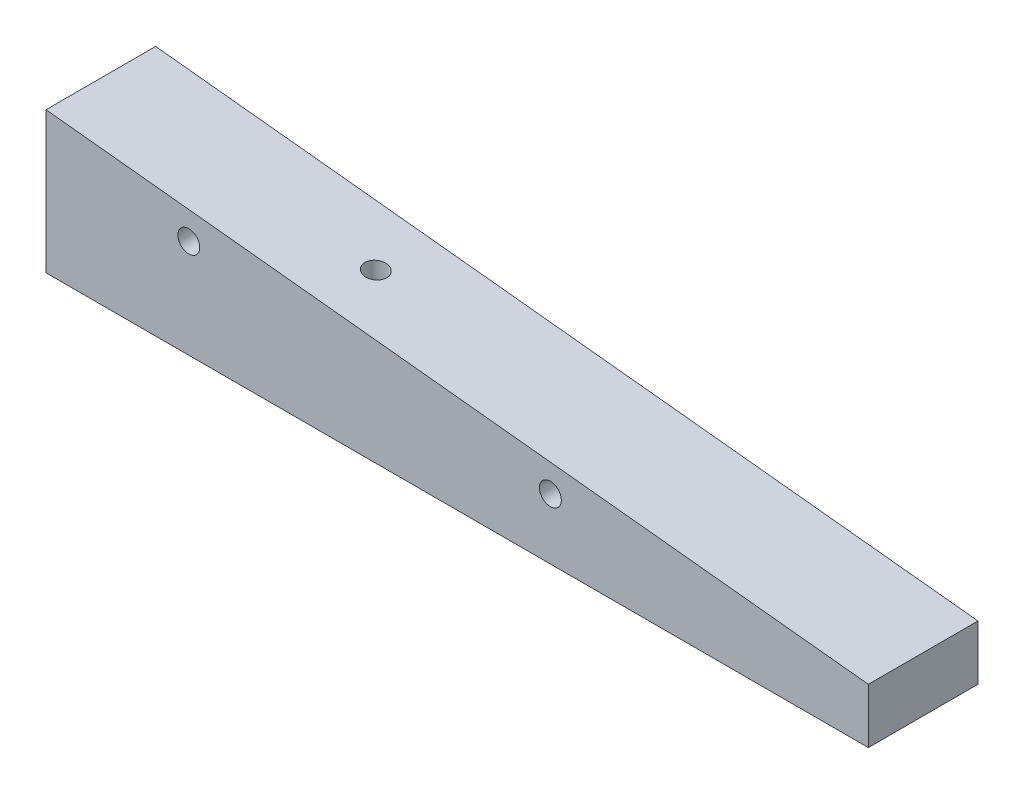
SolidWorks part; units mm, degrees
ref_plane "Front Plane" through (0, 0, 0) normal (0, 0, 1) x (1, 0, 0)
ref_plane "Top Plane" through (0, 0, 0) normal (0, 1, 0) x (1, 0, 0)
ref_plane "Right Plane" through (0, 0, 0) normal (1, 0, 0) x (0, 0, -1)
sketch "Sketch1" plane through (0, 0, 0) normal (0, 0, 1) x (1, 0, 0)
  line L2 (99.8523, 10) -> (-50.1477, 25.7656)
  line L4 (99.8523, 10) -> (99.8523, 0)
  line L5 (99.8523, 0) -> (-50.1477, 0)
  line L6 (-50.1477, 0) -> (-50.1477, 25.7656)
  line L7 (55, 0) -> (-55, 0) construction
  point P0 (0, 0)
  dimension "D1" = 150
  dimension "D2" = 6
  dimension "D3" = 10
extrude "Boss-Extrude1" add sketch "Sketch1" along normal mid plane 20
sketch "Sketch2" plane through (0, 0, 0) normal (0, -1, 0) x (1, 0, 0)
  circle A0 centre (0, 0) radius 2
  dimension "D1" = 4
extrude "Cut-Extrude1" cut sketch "Sketch2" against normal through all both and the other way through all
sketch "Sketch3" plane through (0, 0, -10) normal (0, 0, -1) x (-1, 0, 0)
  line L0 (-42.3716, 16.0415) -> (-41.849, 11.0689) construction
  line L1 (-99.8523, 10) -> (50.1477, 25.7656) construction
  line L2 (23.5813, 22.9734) -> (24.1039, 18.0008) construction
  circle A0 centre (24.1039, 18.0008) radius 2
  circle A1 centre (-41.849, 11.0689) radius 2
  dimension "D5" = 4
  dimension "D6" = 4
  dimension "D1" = 90
  dimension "D2" = 90
  dimension "D3" = 5
  dimension "D4" = 5
extrude "Cut-Extrude2" cut sketch "Sketch3" against normal through all both
